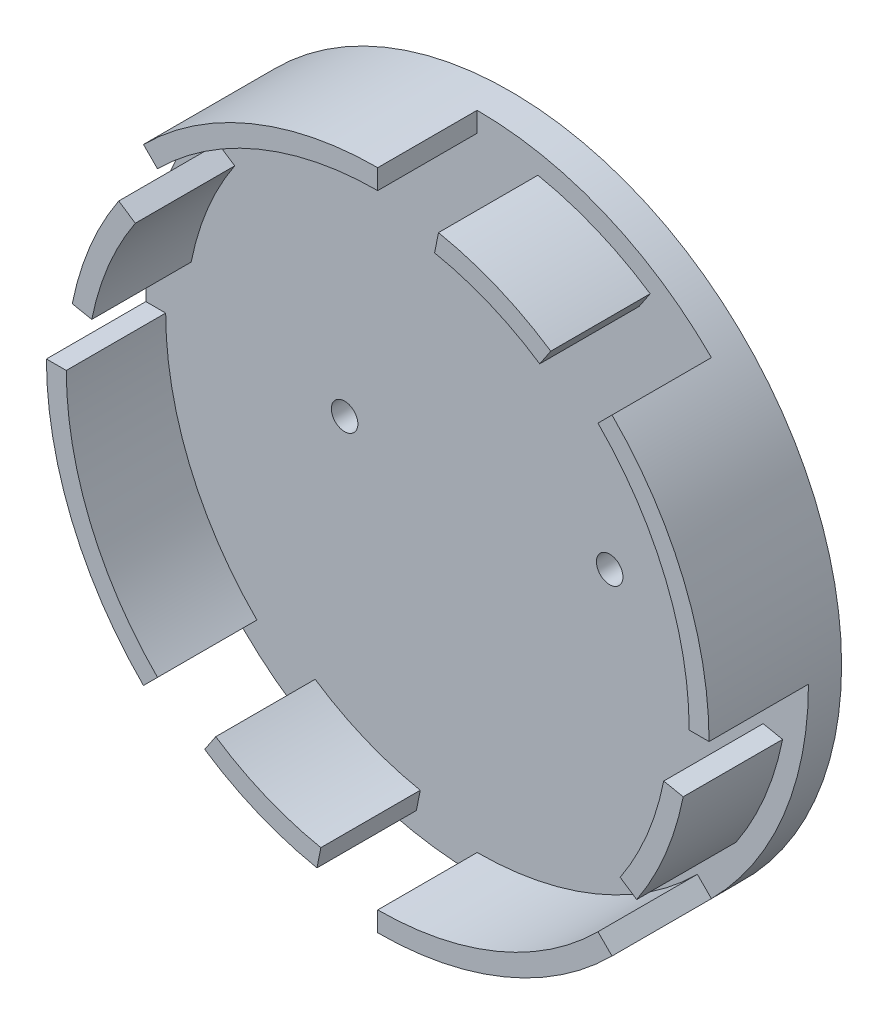
SolidWorks part; units mm, degrees
ref_plane "前视基准面" through (0, 0, 0) normal (0, 0, 1) x (1, 0, 0)
ref_plane "上视基准面" through (0, 0, 0) normal (0, 1, 0) x (1, 0, 0)
ref_plane "右视基准面" through (0, 0, 0) normal (1, 0, 0) x (0, 0, -1)
other "Configuration Table"
sketch "草图1" plane through (0, 0, 0) normal (0, 0, 1) x (1, 0, 0)
  line L0 (-50, 0) -> (50, 0) construction
  circle A0 centre (0, 0) radius 50
  circle A1 centre (-20, 0) radius 2
  circle A2 centre (20, 0) radius 2
  dimension "D1" = 100
  dimension "D4" = 4
  dimension "D5" = 4
  dimension "D2" = 20
  dimension "D3" = 20
extrude "凸台-拉伸1" add sketch "草图1" along normal blind 5
sketch "草图2" plane through (0, 0, 5) normal (0, 0, 1) x (1, 0, 0)
  line L0 (0, 50) -> (0, 47)
  line L1 (-50, 0) -> (-47, 0)
  line L2 (35.3553, 35.3553) -> (33.234, 33.234)
  line L3 (-35.3553, 35.3553) -> (-33.234, 33.234)
  line L4 (33.234, -33.234) -> (35.3553, -35.3553)
  line L5 (0, -47) -> (0, -50)
  line L6 (-33.234, -33.234) -> (-35.3553, -35.3553)
  line L7 (47, 0) -> (50, 0)
  arc A0 (50, 0) -> (35.3553, 35.3553) centre (0, 0) ccw
  arc A1 (-47, 0) -> (-33.234, -33.234) centre (0, 0) ccw
  arc A6 (0, 50) -> (-35.3553, 35.3553) centre (0, 0) ccw
  arc A7 (-50, 0) -> (-35.3553, -35.3553) centre (0, 0) ccw
  arc A8 (0, 47) -> (-33.234, 33.234) centre (0, 0) ccw
  arc A9 (47, 0) -> (33.234, 33.234) centre (0, 0) ccw
  arc A10 (0, -47) -> (33.234, -33.234) centre (0, 0) ccw
  arc A11 (0, -50) -> (35.3553, -35.3553) centre (0, 0) ccw
  point P12 (0, 0)
  dimension "D1" = 94
  dimension "D2" = 45
  dimension "D3" = 45
extrude "凸台-拉伸2" add sketch "草图2" along normal blind 15 contours A8 L3 A6 L0
sketch "草图5" plane through (0, 0, 5) normal (0, 0, 1) x (1, 0, 0)
  line L0 (-35.3553, 35.3553) -> (-33.234, 33.234)
  line L1 (0, 50) -> (0, 47)
  line L2 (-50, 0) -> (-47, 0)
  line L3 (-35.3553, -35.3553) -> (-33.234, -33.234)
  line L4 (33.234, 33.234) -> (35.3553, 35.3553)
  line L5 (0, -47) -> (0, -50)
  line L6 (33.234, -33.234) -> (35.3553, -35.3553)
  line L7 (47, 0) -> (50, 0)
  arc A0 (0, 47) -> (-33.234, 33.234) centre (0, 0) ccw
  arc A1 (0, 50) -> (-35.3553, 35.3553) centre (0, 0) ccw
  arc A2 (47, 0) -> (33.234, 33.234) centre (0, 0) ccw
  arc A3 (50, 0) -> (35.3553, 35.3553) centre (0, 0) ccw
  arc A4 (0, -47) -> (33.234, -33.234) centre (0, 0) ccw
  arc A5 (0, -50) -> (35.3553, -35.3553) centre (0, 0) ccw
  arc A6 (-47, 0) -> (-33.234, -33.234) centre (0, 0) ccw
  arc A7 (-50, 0) -> (-35.3553, -35.3553) centre (0, 0) ccw
  dimension "D1" = 94
  dimension "D2" = 45
  dimension "D3" = 45
extrude "凸台-拉伸3" add sketch "草图5" along normal blind 15
sketch "草图6" plane through (0, 0, 5) normal (0, 0, 1) x (1, 0, 0)
  line L1 (-39.0791, 26.1118) -> (-36.5847, 24.4451)
  line L4 (9.1692, 46.0969) -> (8.584, 43.1546)
  line L5 (26.1118, 39.0791) -> (24.4451, 36.5847)
  line L7 (-46.0969, 9.1692) -> (-43.1546, 8.584)
  line L8 (46.0969, -9.1692) -> (43.1546, -8.584)
  line L9 (39.0791, -26.1118) -> (36.5847, -24.4451)
  line L10 (-9.1692, -46.0969) -> (-8.584, -43.1546)
  line L11 (-26.1118, -39.0791) -> (-24.4451, -36.5847)
  arc A0 (26.1118, 39.0791) -> (9.1692, 46.0969) centre (0, 0) ccw
  arc A4 (-39.0791, 26.1118) -> (-46.0969, 9.1692) centre (0, 0) ccw
  arc A5 (-36.5847, 24.4451) -> (-43.1546, 8.584) centre (0, 0) ccw
  arc A6 (24.4451, 36.5847) -> (8.584, 43.1546) centre (0, 0) ccw
  arc A7 (39.0791, -26.1118) -> (46.0969, -9.1692) centre (0, 0) ccw
  arc A8 (36.5847, -24.4451) -> (43.1546, -8.584) centre (0, 0) ccw
  arc A9 (-26.1118, -39.0791) -> (-9.1692, -46.0969) centre (0, 0) ccw
  arc A10 (-24.4451, -36.5847) -> (-8.584, -43.1546) centre (0, 0) ccw
  point P24 (0, 0)
  dimension "D1" = 4
extrude "凸台-拉伸4" add sketch "草图6" along normal blind 15
